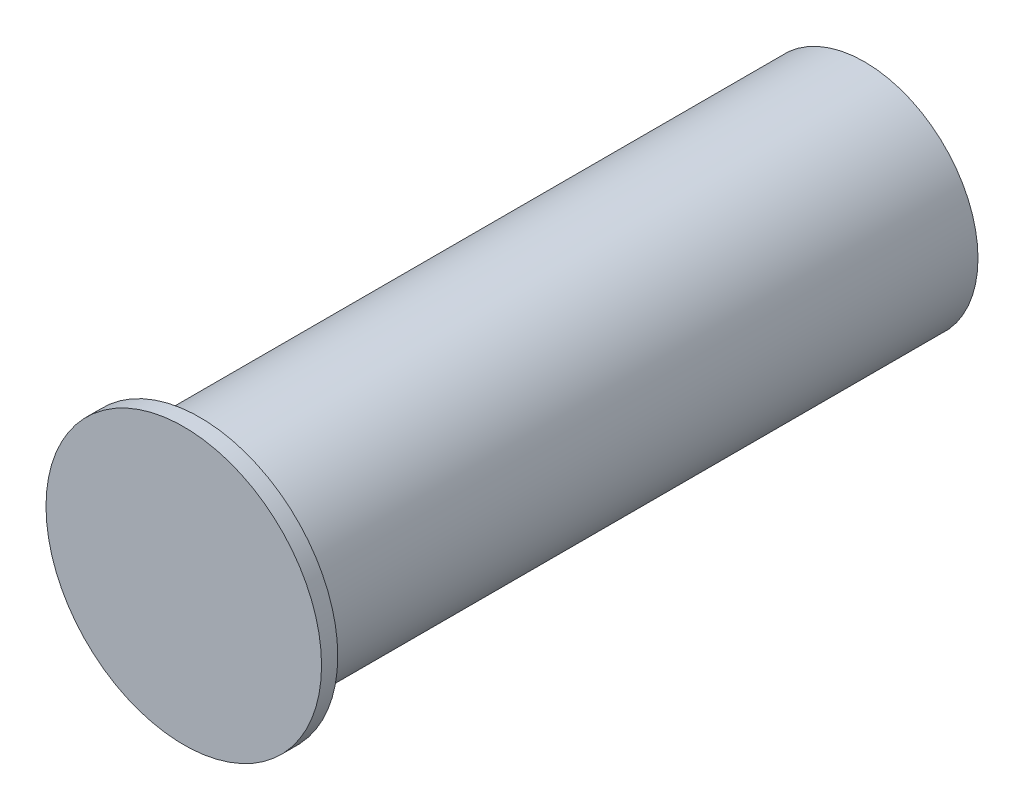
SolidWorks part; units mm, degrees
ref_plane "Front Plane" through (0, 0, 0) normal (0, 0, 1) x (1, 0, 0)
ref_plane "Top Plane" through (0, 0, 0) normal (0, 1, 0) x (1, 0, 0)
ref_plane "Right Plane" through (0, 0, 0) normal (1, 0, 0) x (0, 0, -1)
sketch "Sketch1" plane through (0, 0, 0) normal (0, 0, 1) x (1, 0, 0)
  circle A0 centre (0, 0) radius 1.778
  dimension "D1" = 3.556
extrude "Boss-Extrude1" add sketch "Sketch1" against normal blind 10.414
sketch "Sketch2" plane through (0, 0, 0) normal (0, 0, 1) x (1, 0, 0)
  circle A0 centre (0, 0) radius 2.159
  dimension "D1" = 4.318
extrude "Boss-Extrude2" add sketch "Sketch2" along normal blind 0.254
